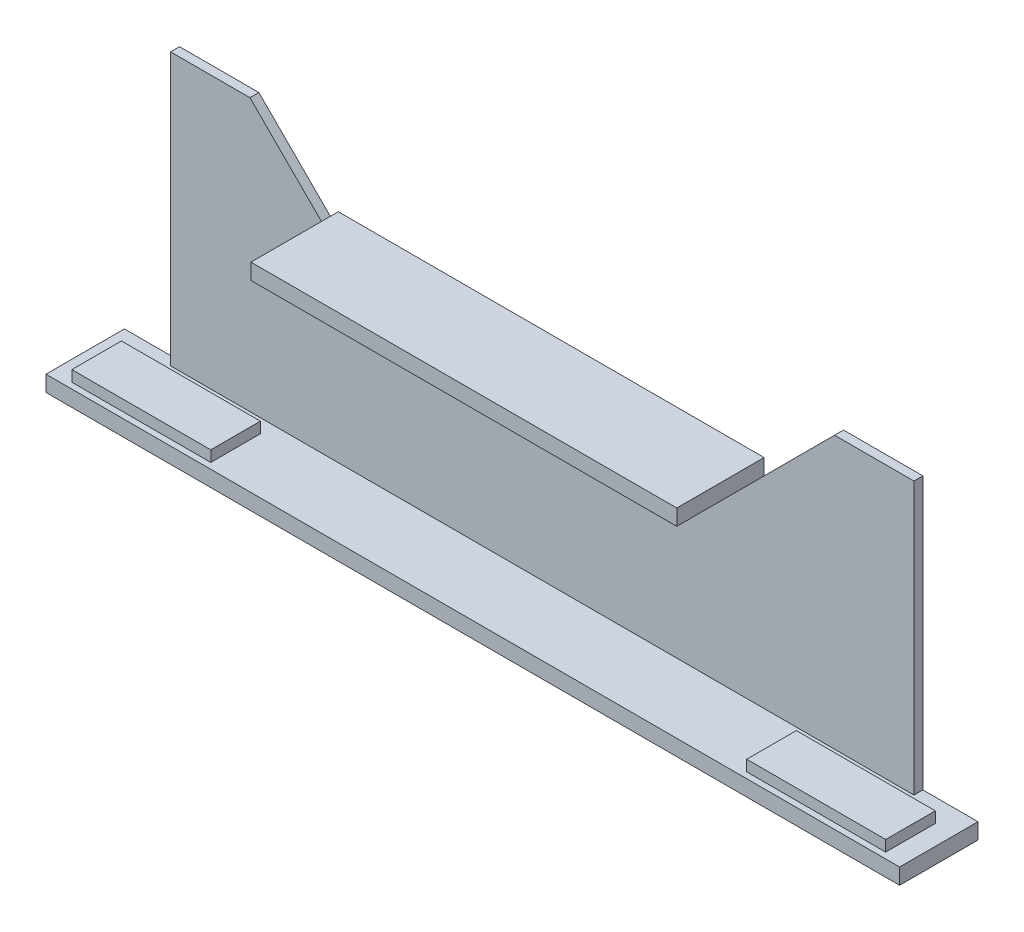
SolidWorks part; units mm, degrees
ref_plane "前视基准面" through (0, 0, 0) normal (0, 0, 1) x (1, 0, 0)
ref_plane "上视基准面" through (0, 0, 0) normal (0, 1, 0) x (1, 0, 0)
ref_plane "右视基准面" through (0, 0, 0) normal (1, 0, 0) x (0, 0, -1)
sketch "草图1" plane through (0, 0, 0) normal (0, 0, 1) x (1, 0, 0)
  line L0 (-1000, 0) -> (49000, 0) construction
  line L1 (0, -1000) -> (0, 49000) construction
  line L2 (0, 0) -> (860, 0)
  line L3 (55.5, -562.2618) -> (55.5, 49437.7382) construction
  line L4 (-1038.7035, 16) -> (48961.2965, 16) construction
  line L5 (860, -1000) -> (860, 49000) construction
  line L6 (804.5, -950.8793) -> (804.5, 49049.1207) construction
  line L7 (-663.1285, 290) -> (49336.8715, 290) construction
  line L8 (-660.6051, 210) -> (49339.3949, 210) construction
  line L9 (0, 0) -> (0, 16)
  line L10 (0, 16) -> (55.5, 16)
  line L11 (860, 0) -> (860, 16)
  line L12 (860, 16) -> (804.5, 16)
  line L13 (55.5, 290) -> (135.5, 290)
  line L14 (804.5, 290) -> (724.5, 290)
  line L15 (55.5, 16) -> (55.5, 290)
  line L16 (804.5, 16) -> (804.5, 290)
  line L17 (135.5, 290) -> (215.5, 210) construction
  line L18 (724.5, 290) -> (644.5, 210) construction
  line L19 (135.5, 290) -> (215.5, 210)
  line L20 (724.5, 290) -> (644.5, 210)
  line L21 (215.5, 210) -> (215.5, 226)
  line L22 (95.5, -794.5532) -> (95.5, 49205.4468) construction
  line L23 (764.5, -804.9005) -> (764.5, 49195.0995) construction
  line L24 (-871.0333, 90) -> (49128.9667, 90) construction
  line L25 (-452.5392, 170) -> (49547.4608, 170) construction
  line L26 (-439.8924, 250) -> (49560.1076, 250) construction
  line L27 (644.5, 210) -> (644.5, 226)
  line L28 (215.5, 226) -> (644.5, 226)
  circle A0 centre (95.5, 90) radius 13
  circle A1 centre (95.5, 170) radius 13
  circle A2 centre (95.5, 250) radius 13
  circle A3 centre (764.5, 90) radius 13
  circle A4 centre (764.5, 170) radius 13
  circle A5 centre (764.5, 250) radius 13
  point P10 (0, 16)
  point P15 (860, 16)
  point P17 (804.5, 16)
  point P18 (55.5, 16)
  point P22 (55.5, 290)
  point P28 (804.5, 290)
  point P44 (764.5, 90)
  point P46 (764.5, 170)
  point P47 (764.5, 250)
  point P48 (95.5, 90)
  point P49 (95.5, 170)
  point P50 (95.5, 250)
  dimension "D17" = 26
  dimension "D18" = 26
  dimension "D19" = 26
  dimension "D20" = 26
  dimension "D21" = 26
  dimension "D22" = 26
  dimension "D1" = 860
  dimension "D2" = 55.5
  dimension "D3" = 16
  dimension "D4" = 860
  dimension "D5" = 55.5
  dimension "D6" = 290
  dimension "D7" = 210
  dimension "D8" = 80
  dimension "D9" = 80
  dimension "D10" = 45
  dimension "D11" = 45
  dimension "D12" = 40
  dimension "D13" = 40
  dimension "D14" = 90
  dimension "D15" = 80
  dimension "D16" = 80
  dimension "D23" = 16
  dimension "D24" = 16
extrude "凸台-拉伸2" add sketch "草图1" along normal blind 9
sketch "草图3" plane through (0, 0, 9) normal (0, 0, 1) x (1, 0, 0)
  line L0 (0, 0) -> (860, 0)
  line L1 (0, 0) -> (0, 16)
  line L2 (0, 16) -> (860, 16)
  line L3 (860, 16) -> (860, 0)
extrude "凸台-拉伸3" add sketch "草图3" along normal blind 70
sketch "草图4" plane through (0, 16, 0) normal (0, 1, 0) x (1, 0, 0)
  line L0 (-1008.5696, -48) -> (48991.4304, -48) construction
  line L1 (55.5, 0) -> (0, 0) construction
  line L3 (20, -1060.4184) -> (20, 48939.5816) construction
  line L4 (0, -79) -> (0, 0) construction
  line L5 (-980, -23) -> (49020, -23) construction
  line L7 (20, -23) -> (160, -23)
  line L8 (20, -23) -> (20, -73)
  line L9 (20, -73) -> (160, -73)
  line L10 (160, -23) -> (160, -73)
  point P9 (20, -23)
  dimension "D1" = 48
  dimension "D2" = 20
  dimension "D3" = 25
  dimension "D4" = 140
  dimension "D5" = 50
extrude "凸台-拉伸5" add sketch "草图4" along normal blind 11
sketch "草图5" plane through (0, 27, 0) normal (0, 1, 0) x (1, 0, 0)
  line L0 (-938.461, -48) -> (49061.539, -48) construction
  line L1 (55.5, 0) -> (0, 0) construction
  line L2 (40, -1048) -> (40, 48952) construction
  line L3 (0, -79) -> (0, 0) construction
  circle A0 centre (40, -48) radius 13
  point P10 (40, -48)
  dimension "D3" = 26
  dimension "D1" = 48
  dimension "D2" = 40
extrude "切除-拉伸2" cut sketch "草图5" against normal through all
pattern_linear "阵列(线性)1" count 2 spacing 80 along (1, 0, 0) of "切除-拉伸2"
sketch "草图6" plane through (0, 16, 0) normal (0, 1, 0) x (1, 0, 0)
  line L0 (840, -1040.034) -> (840, 48959.966) construction
  line L1 (860, -79) -> (860, 0) construction
  line L2 (-442.9077, -23) -> (49557.0923, -23) construction
  line L3 (860, 0) -> (804.5, 0) construction
  line L5 (840, -23) -> (700, -23)
  line L6 (840, -23) -> (840, -73)
  line L7 (840, -73) -> (700, -73)
  line L8 (700, -23) -> (700, -73)
  point P8 (840, -23)
  dimension "D1" = 20
  dimension "D2" = 23
  dimension "D3" = 140
  dimension "D4" = 50
extrude "凸台-拉伸6" add sketch "草图6" along normal blind 6
sketch "草图7" plane through (0, 22, 0) normal (0, 1, 0) x (1, 0, 0)
  line L0 (-220.763, -48) -> (49779.237, -48) construction
  line L1 (860, 0) -> (804.5, 0) construction
  line L2 (820, -1054.986) -> (820, 48945.014) construction
  line L3 (860, -79) -> (860, 0) construction
  circle A0 centre (820, -48) radius 13
  point P8 (820, -48)
  dimension "D3" = 26
  dimension "D1" = 48
  dimension "D2" = 40
extrude "切除-拉伸3" cut sketch "草图7" against normal through all
pattern_linear "阵列(线性)2" count 2 spacing 80 along (-1, 0, 0) of "切除-拉伸3"
sketch "草图10" plane through (0, 0, 9) normal (0, 0, 1) x (1, 0, 0)
  line L1 (215.5, 226) -> (644.5, 226)
  line L2 (215.5, 226) -> (215.5, 210)
  line L3 (215.5, 210) -> (644.5, 210)
  line L4 (644.5, 226) -> (644.5, 210)
  dimension "D1" = 429
  dimension "D2" = 16
extrude "凸台-拉伸8" add sketch "草图10" along normal blind 79
sketch "草图11" plane through (0, 0, 9) normal (0, 0, 1) x (1, 0, 0)
  line L0 (55.5, 290) -> (135.5, 290)
  line L1 (135.5, 290) -> (215.5, 210)
  line L2 (215.5, 210) -> (644.5, 210)
  line L3 (644.5, 210) -> (724.5, 290)
  line L4 (724.5, 290) -> (804.5, 290)
  line L5 (804.5, 290) -> (804.5, 16)
  line L6 (700, 16) -> (840, 16) construction
  line L7 (860, 16) -> (0, 16) construction
  line L8 (804.5, 16) -> (55.5, 16)
  line L9 (55.5, 16) -> (55.5, 290)
  line L10 (55.5, 290) -> (55.5, 16) construction
  line L11 (804.5, 16) -> (55.5, 16) construction
extrude "凸台-拉伸9" add sketch "草图11" against normal blind 9
sketch "草图12" plane through (0, 27, 0) normal (0, 1, 0) x (1, 0, 0)
  line L1 (20, -23) -> (160, -23)
  line L2 (20, -23) -> (20, -73)
  line L3 (20, -73) -> (160, -73)
  line L4 (160, -23) -> (160, -73)
  line L5 (700, -23) -> (840, -23)
  line L6 (700, -23) -> (700, -73)
  line L7 (700, -73) -> (840, -73)
  line L8 (840, -23) -> (840, -73)
extrude "凸台-拉伸10" add sketch "草图12" against normal blind 27
